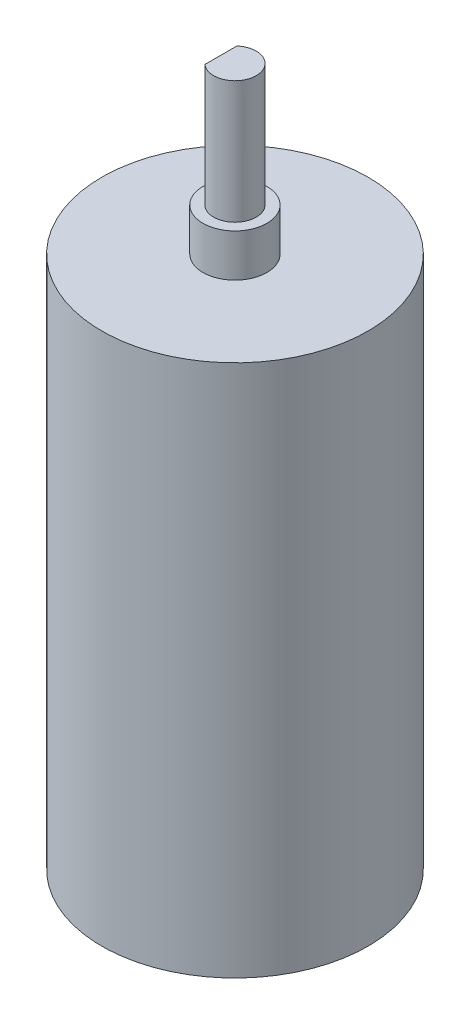
SolidWorks part; units mm, degrees
ref_plane "Front Plane" through (0, 0, 0) normal (0, 0, 1) x (1, 0, 0)
ref_plane "Top Plane" through (0, 0, 0) normal (0, 1, 0) x (1, 0, 0)
ref_plane "Right Plane" through (0, 0, 0) normal (1, 0, 0) x (0, 0, -1)
sketch "Sketch1" plane through (0, 0, 0) normal (0, 0, 1) x (1, 0, 0)
  line L0 (0, 0) -> (0, 179226.769) construction
  line L1 (0, 65.5) -> (-2, 65.5)
  line L2 (-2, 65.5) -> (-2, 54)
  line L3 (-2, 54) -> (-3, 54)
  line L4 (-3, 54) -> (-3, 50)
  line L5 (-3, 50) -> (-12.5, 50)
  line L6 (-12.5, 50) -> (-12.5, 0)
  line L7 (-12.5, 0) -> (0, 0)
  line L8 (0, 0) -> (0, 65.5)
  dimension "D1" = 12.5
  dimension "D2" = 50
  dimension "D3" = 4
  dimension "D4" = 11.5
  dimension "D5" = 3
  dimension "D6" = 2
revolve "Revolve1" add sketch "Sketch1" angle 360 about L0
sketch "Sketch2" plane through (0, 65.5, 0) normal (0, 1, 0) x (1, 0, 0)
  line L0 (-1.3229, 1.5) -> (-1.3229, -1.5)
  circle A0 centre (0, 0) radius 2 construction
  arc A1 (-1.3229, 1.5) -> (-1.3229, -1.5) centre (0, 0) ccw
  dimension "D1" = 3
extrude "Cut-Extrude1" cut sketch "Sketch2" against normal blind 10
